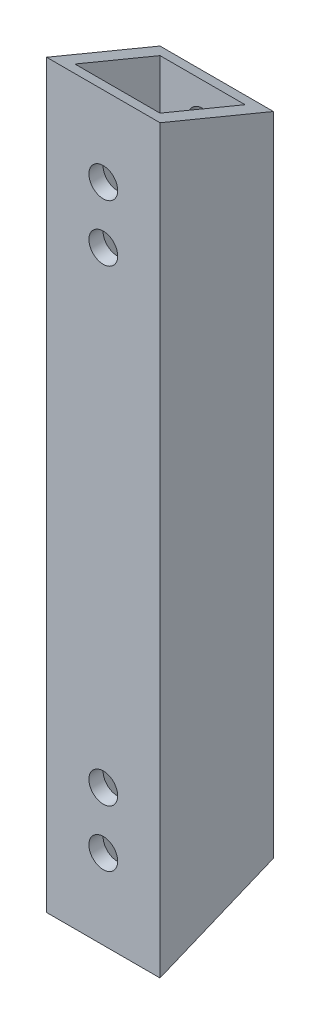
SolidWorks part; units mm, degrees
material "6061-T6 (SS)"
ref_plane "Front Plane" through (0, 0, 0) normal (0, 0, 1) x (1, 0, 0)
ref_plane "Top Plane" through (0, 0, 0) normal (0, 1, 0) x (1, 0, 0)
ref_plane "Right Plane" through (0, 0, 0) normal (1, 0, 0) x (0, 0, -1)
sketch "Sketch1" plane through (0, 0, 0) normal (0, 1, 0) x (1, 0, 0)
  line L1 (-9.525, -9.525) -> (9.525, -9.525)
  line L2 (-9.525, -9.525) -> (-9.525, 9.525)
  line L3 (-9.525, 9.525) -> (9.525, 9.525)
  line L4 (9.525, -9.525) -> (9.525, 9.525)
  line L5 (-9.525, -9.525) -> (9.525, 9.525) construction
  line L6 (-9.525, 9.525) -> (9.525, -9.525) construction
  line L7 (-12.7, -12.7) -> (12.7, -12.7)
  line L8 (-12.7, -12.7) -> (-12.7, 12.7)
  line L9 (-12.7, 12.7) -> (12.7, 12.7)
  line L10 (12.7, -12.7) -> (12.7, 12.7)
  line L11 (-12.7, -12.7) -> (12.7, 12.7) construction
  line L12 (-12.7, 12.7) -> (12.7, -12.7) construction
  point P0 (0, 0)
  point P6 (0, 0)
  dimension "D1" = 3.175
  dimension "D2" = 25.4
extrude "Boss-Extrude1" add sketch "Sketch1" along normal mid plane 165.862
sketch "Sketch2" plane through (12.7, 0, 0) normal (1, 0, 0) x (0, 0, -1)
  line L0 (-12.7, 82.931) -> (12.7, 72.41)
  line L1 (-12.7, 0) -> (12.7, 0) construction
  line L2 (-12.7, -82.931) -> (12.7, -72.41)
  line L4 (-12.7, -82.931) -> (12.7, -82.931)
  line L5 (12.7, -82.931) -> (12.7, 82.931)
  line L6 (12.7, 82.931) -> (-12.7, 82.931)
  line L7 (-12.7, 82.931) -> (-12.7, -82.931)
  line L8 (-12.7, -82.931) -> (12.7, -82.931)
  line L9 (12.7, -82.931) -> (12.7, 82.931)
  line L10 (12.7, 82.931) -> (-12.7, 82.931)
  line L11 (-12.7, 82.931) -> (-12.7, -82.931)
  line M7 (-12.7, -82.931) -> (12.7, -82.931)
  line M8 (12.7, -82.931) -> (12.7, 82.931)
  line M9 (12.7, 82.931) -> (-12.7, 82.931)
  dimension "D2" = 22.5
  dimension "D1" = 0
extrude "Cut-Extrude1" cut sketch "Sketch2" against normal through all contours L0 M9 M8 | L2 M7 M8
sketch "Sketch3" plane through (0, 0, -12.7) normal (0, 0, -1) x (-1, 0, 0)
  line L0 (12.7, -72.41) -> (-12.7, -72.41) construction
  line L1 (0, -72.41) -> (0, 0) construction
  line L2 (0, 0) -> (12.7, 0) construction
  line L3 (12.7, 72.41) -> (12.7, -72.41) construction
  circle A0 centre (0, -65.044) radius 3.2224
  circle A1 centre (0, -52.344) radius 3.2224
  circle A2 centre (0, 65.044) radius 3.2224
  circle A3 centre (0, 52.344) radius 3.2224
  dimension "D2" = 6.4448
  dimension "D1" = 7.366
  dimension "D3" = 12.7
extrude "Cut-Extrude2" cut sketch "Sketch3" against normal through all
